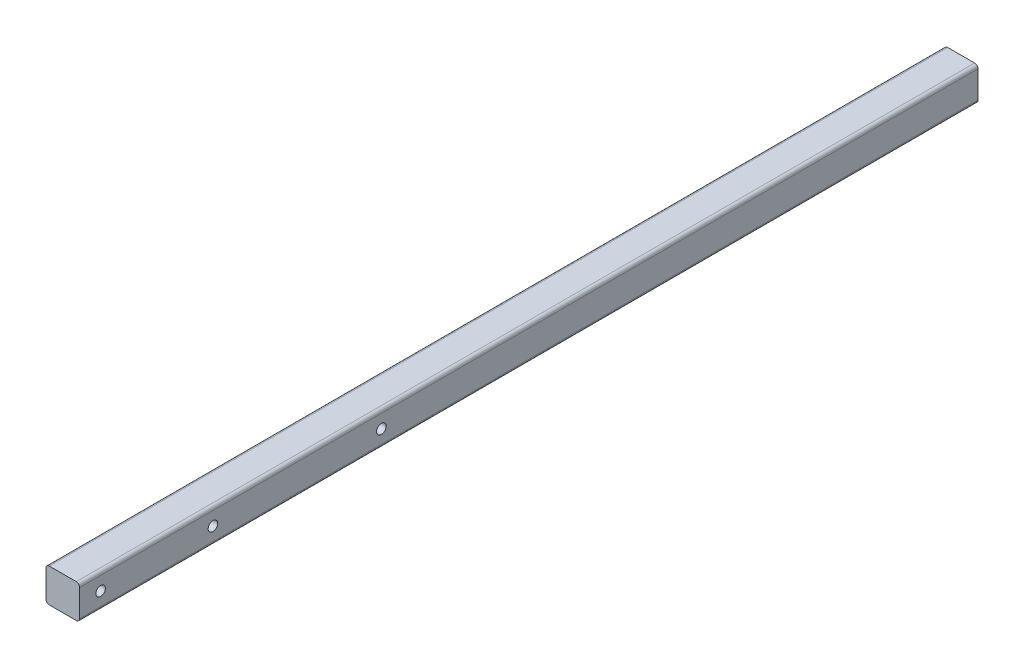
SolidWorks part; units mm, degrees
ref_plane "Front Plane" through (0, 0, 0) normal (0, 0, 1) x (1, 0, 0)
ref_plane "Top Plane" through (0, 0, 0) normal (0, 1, 0) x (1, 0, 0)
ref_plane "Right Plane" through (0, 0, 0) normal (1, 0, 0) x (0, 0, -1)
ref_plane "Plane1" through (-284.1, 0, 0) normal (1, 0, 0) x (0, 0, -1)
sketch "Sketch1" plane through (-284.1, 0, 0) normal (1, 0, 0) x (0, 0, -1)
  line L0 (-1059.7538, 537.881) -> (-1059.7538, 507.881)
  line L1 (-1059.7538, 507.881) -> (-259.7538, 507.881)
  line L2 (-259.7538, 507.881) -> (-259.7538, 537.881)
  line L3 (-259.7538, 537.881) -> (-1059.7538, 537.881)
  dimension "D1" = 800
  dimension "D2" = 30
extrude "Boss-Extrude1" add sketch "Sketch1" against normal blind 30
hole_wizard "Ø8.5 (8.5) Diameter Hole1" positions "Sketch3" profile "Sketch2" hole size "Ø8.5" standard "ANSI Metric" end condition through all
sketch "Sketch3" plane through (-284.1, 0, 0) normal (1, 0, 0) x (0, 0, -1)
  line L0 (-259.7538, 507.881) -> (-259.7538, 537.881) construction
  line L1 (-1059.7538, 507.881) -> (-259.7538, 507.881) construction
  line L2 (-1041.0917, 522.881) -> (-256.9149, 522.881) construction
  point P0 (-791.0917, 522.881)
  point P1 (-941.0917, 522.881)
  point P2 (-1041.0917, 522.881)
  dimension "D1" = 531.3379
  dimension "D2" = 150
  dimension "D3" = 100
  dimension "D4" = 15
sketch "Sketch2" plane through (-284.1, 522.881, 791.0917) normal (0, 1, 0) x (0, 0, -1)
  line L0 (0, 0) -> (0, 30)
  line L1 (0, 30) -> (4.25, 30)
  line L2 (4.25, 30) -> (4.25, 0)
  line L5 (4.25, 0) -> (0, 0)
  line L11 (0, -6.35) -> (0, 107.95) construction
  dimension "Thru Hole Dia." = 8.5
  dimension "Thru Hole Depth" = 30
fillet "Fillet1" radius 3 4 edges at (-284.1, 507.881, 659.7538) (-314.1, 507.881, 659.7538) (-314.1, 537.881, 659.7538) (-284.1, 537.881, 659.7538)
